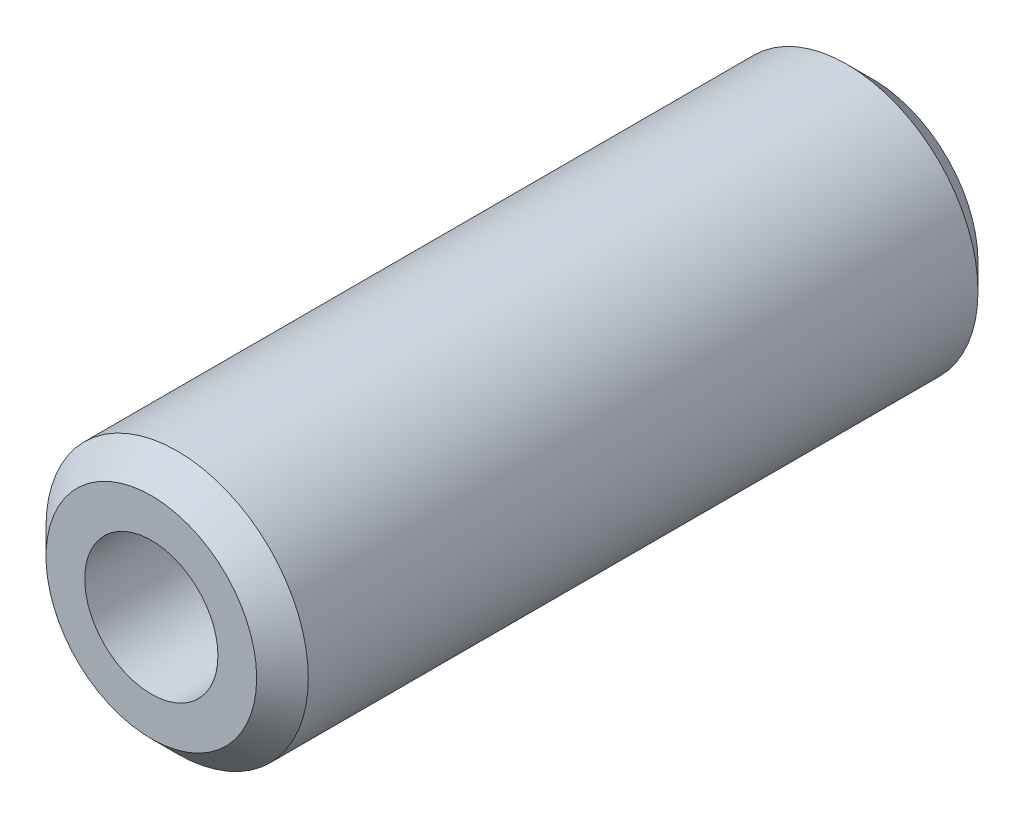
SolidWorks part; units mm, degrees
ref_plane "Front Plane" through (0, 0, 0) normal (0, 0, 1) x (1, 0, 0)
ref_plane "Top Plane" through (0, 0, 0) normal (0, 1, 0) x (1, 0, 0)
ref_plane "Right Plane" through (0, 0, 0) normal (1, 0, 0) x (0, 0, -1)
sketch "Sketch1" plane through (0, 0, 0) normal (0, 0, 1) x (1, 0, 0)
  circle A0 centre (0, 0) radius 6.45
  circle A1 centre (0, 0) radius 12.7
  dimension "D1" = 25.4
  dimension "D2" = 12.9
extrude "Boss-Extrude1" add sketch "Sketch1" along normal mid plane 69.85
chamfer "Chamfer1" distance 2.5 angle 45 2 edges at (12.7, 0, -34.925) (12.7, 0, 34.925)
